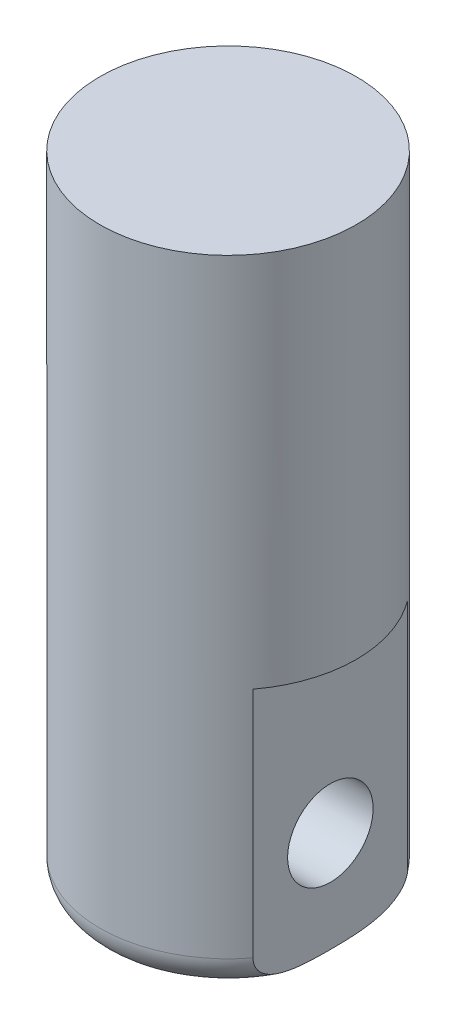
SolidWorks part; units mm, degrees
ref_plane "Спереди" through (0, 0, 0) normal (0, 0, 1) x (1, 0, 0)
ref_plane "Сверху" through (0, 0, 0) normal (0, 1, 0) x (1, 0, 0)
ref_plane "Справа" through (0, 0, 0) normal (1, 0, 0) x (0, 0, -1)
sketch "Эскиз1" plane through (0, 0, 0) normal (0, 1, 0) x (1, 0, 0)
  circle A0 centre (0, 0) radius 12
  dimension "D1" = 24
extrude "Вытянуть1" add sketch "Эскиз1" along normal blind 60
fillet "Скругление1" radius 3 1 edges at (0, 0, 12)
sketch "Эскиз2" plane through (0, 0, 0) normal (0, 0, 1) x (1, 0, 0)
  line L0 (-14, 24.7729) -> (-9.5712, 24.7729)
  line L2 (-9.5712, 24.7729) -> (-9.5712, -5.055)
  line L3 (-9.5712, -5.055) -> (-14, -5.055)
  line L4 (-14, -5.055) -> (-14, 24.7729)
  line L5 (0, 0) -> (0, 21.2905) construction
  line L6 (9.5712, -5.055) -> (14, -5.055)
  line L7 (14, -5.055) -> (14, 24.7729)
  line L8 (9.5712, 24.7729) -> (9.5712, -5.055)
  line L9 (14, 24.7729) -> (9.5712, 24.7729)
  dimension "D1" = 14
  dimension "D2" = 9.5712
  dimension "D3" = 14
  dimension "D4" = 24.7729
  dimension "D5" = 5.055
extrude "Вырез-Вытянуть1" cut sketch "Эскиз2" against normal mid plane 80
sketch "Эскиз6" plane through (-9.5712, 0, 0) normal (-1, 0, 0) x (0, 0, 1)
  circle A0 centre (0, 9.5) radius 4
extrude "Вырез-Вытянуть2" cut sketch "Эскиз6" against normal mid plane 100
